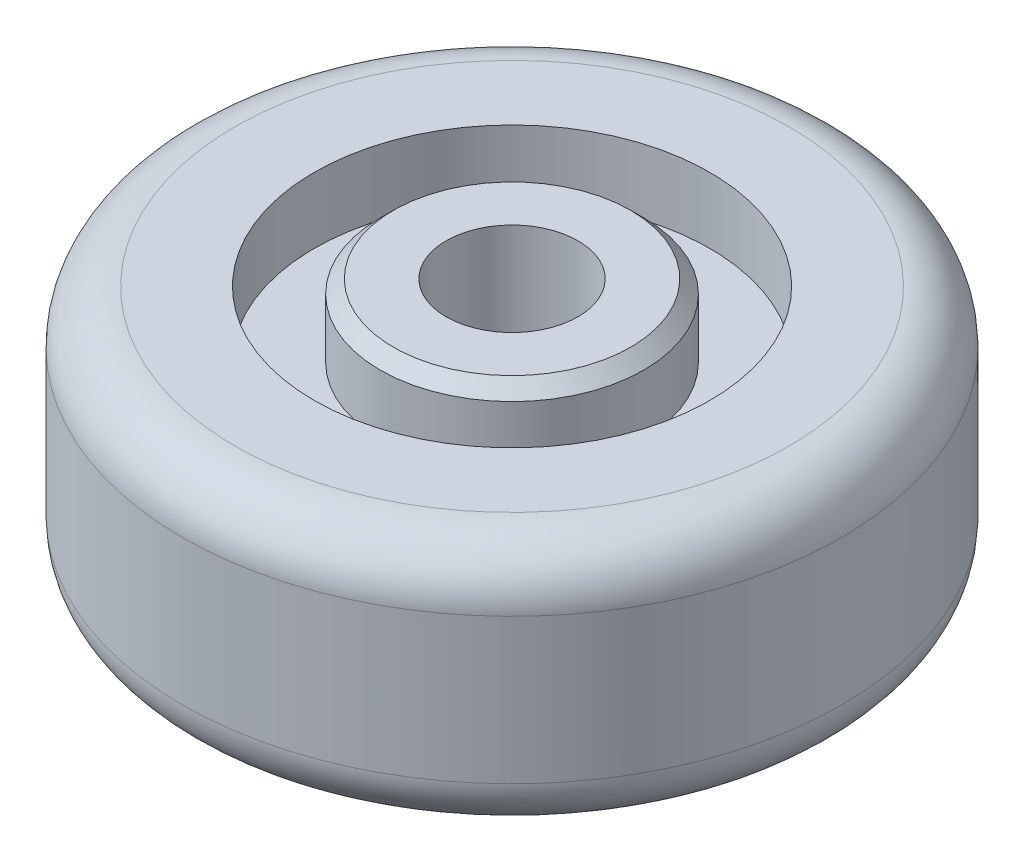
SolidWorks part; units mm, degrees
ref_plane "Front Plane" through (0, 0, 0) normal (0, 0, 1) x (1, 0, 0)
ref_plane "Top Plane" through (0, 0, 0) normal (0, 1, 0) x (1, 0, 0)
ref_plane "Right Plane" through (0, 0, 0) normal (1, 0, 0) x (0, 0, -1)
sketch "Sketch2" plane through (0, 0, 0) normal (1, 0, 0) x (0, 0, -1)
  line L0 (0, 38.5518) -> (0, -36.2674) construction
  line L1 (0, 44.2539) -> (0, -44.2539) construction
  line L2 (10, 10) -> (10, 4.5)
  line L3 (10, 4.5) -> (15, 4.5)
  line L4 (15, 4.5) -> (15, 9.5)
  line L5 (15, 9.5) -> (25, 9.5)
  line L6 (25, 9.5) -> (25, -9.5)
  line L7 (25, -9.5) -> (15, -9.5)
  line L8 (15, -9.5) -> (15, -4.5)
  line L9 (15, -4.5) -> (10, -4.5)
  line L10 (10, -4.5) -> (10, -10)
  line L11 (10, -10) -> (5, -10)
  line L12 (5, -10) -> (5, 10)
  line L13 (5, 10) -> (10, 10)
  line L14 (55, 0) -> (-55, 0) construction
  point P7 (25, 0)
  point P20 (5, 0)
  dimension "D1" = 19
  dimension "D2" = 25
  dimension "D3" = 5
  dimension "D4" = 5
  dimension "D5" = 10
  dimension "D6" = 20
  dimension "D7" = 5
revolve "Revolve1" add sketch "Sketch2" angle 360 about L0
fillet "Fillet1" radius 4 3 edges at (0, 9.5, 25) (0, -9.5, 15) (0, -9.5, 25)
chamfer "Chamfer1" distance 1 angle 45 2 edges at (0, 10, 10) (0, -10, 10)
